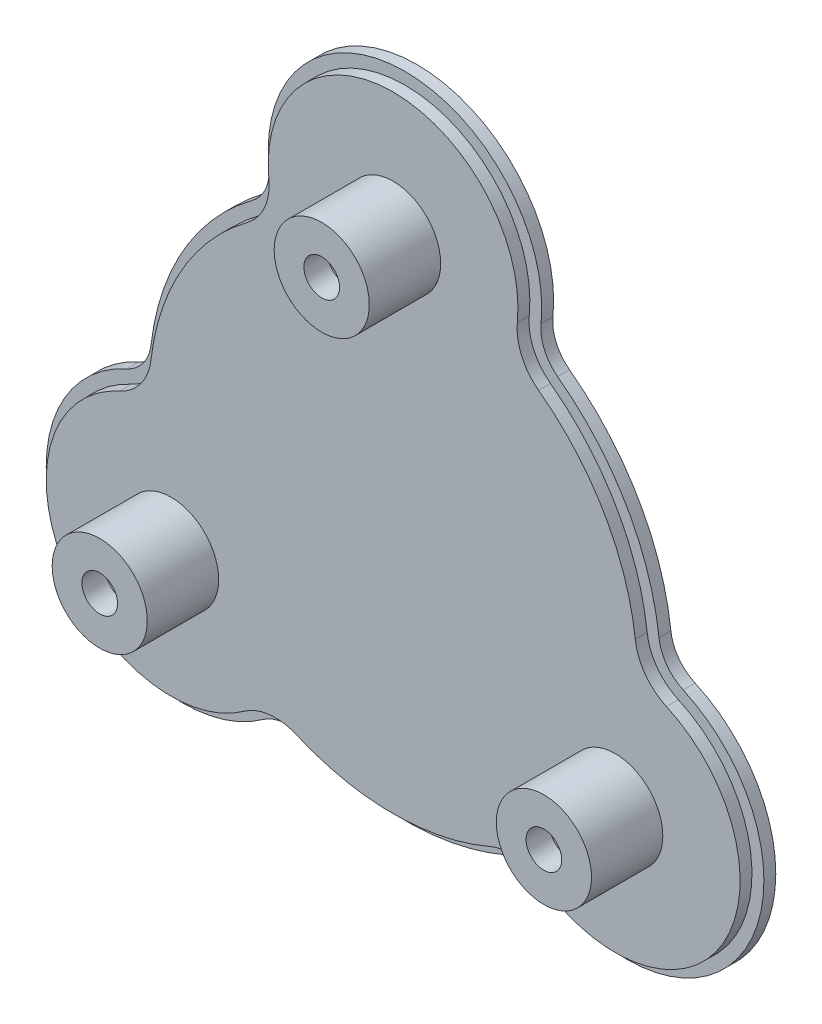
SolidWorks part; units mm, degrees
material "PE Low Density Film"
ref_plane "Front Plane" through (0, 0, 0) normal (0, 0, 1) x (1, 0, 0)
ref_plane "Top Plane" through (0, 0, 0) normal (0, 1, 0) x (1, 0, 0)
ref_plane "Right Plane" through (0, 0, 0) normal (1, 0, 0) x (0, 0, -1)
sketch "Sketch1" plane through (0, 0, 0) normal (0, 0, 1) x (1, 0, 0)
  arc A1 (22.8772, 40.8196) -> (-22.8904, 40.8122) centre (-0.007, 43.1247) ccw
  circle A2 centre (-0.007, 43.1247) radius 5.5
  arc A3 (23.9122, -40.222) -> (46.7896, -0.5824) centre (37.3506, -21.5563) ccw
  circle A4 centre (37.3506, -21.5563) radius 5.5
  arc A5 (-46.7894, -0.5976) -> (-23.8991, -40.2298) centre (-37.3436, -21.5684) ccw
  circle A6 centre (-37.3436, -21.5684) radius 5.5
  arc A7 (-25.6753, 34.4932) -> (-42.7112, 4.975) centre (0, 0) ccw
  arc A8 (42.7096, 4.9888) -> (25.6641, 34.5015) centre (0, 0) ccw
  arc A9 (-17.0343, -39.482) -> (17.0471, -39.4765) centre (0, 0) ccw
  arc A10 (22.8772, 40.8196) -> (25.6641, 34.5015) centre (29.842, 40.118) ccw
  arc A11 (42.7096, 4.9888) -> (46.7896, -0.5824) centre (49.6623, 5.801) ccw
  arc A12 (23.9122, -40.222) -> (17.0471, -39.4765) centre (19.8223, -45.9029) ccw
  arc A13 (-17.0343, -39.482) -> (-23.8991, -40.2298) centre (-19.8074, -45.9093) ccw
  arc A14 (-46.7894, -0.5976) -> (-42.7112, 4.975) centre (-49.6642, 5.7849) ccw
  arc A15 (-25.6753, 34.4932) -> (-22.8904, 40.8122) centre (-29.855, 40.1084) ccw
  point P14 (0, 0)
  point P23 (-20.8553, -37.6039)
  dimension "D2" = 46
  dimension "D3" = 11
  dimension "D1" = 7
  dimension "D4" = 3
extrude "Boss-Extrude1" add sketch "Sketch1" along normal blind 4
sketch "Sketch2" plane through (0, 0, 4) normal (0, 0, 1) x (1, 0, 0)
  arc A0 (-24.4811, 32.8889) -> (-40.7247, 4.7436) centre (0, 0) ccw
  arc A1 (-45.968, -2.4211) -> (-40.7247, 4.7436) centre (-49.6642, 5.7849) ccw
  arc A2 (-45.968, -2.4211) -> (-25.0682, -38.6071) centre (-37.3436, -21.5684) ccw
  arc A3 (-16.242, -37.6457) -> (-25.0682, -38.6071) centre (-19.8074, -45.9093) ccw
  arc A4 (-16.242, -37.6457) -> (16.2543, -37.6404) centre (0, 0) ccw
  arc A5 (25.0808, -38.5989) -> (16.2543, -37.6404) centre (19.8223, -45.9029) ccw
  arc A6 (25.0808, -38.5989) -> (45.9688, -2.4062) centre (37.3506, -21.5563) ccw
  arc A7 (40.7231, 4.7568) -> (45.9688, -2.4062) centre (49.6623, 5.801) ccw
  arc A8 (40.7231, 4.7568) -> (24.4704, 32.8968) centre (0, 0) ccw
  arc A9 (20.8873, 41.02) -> (24.4704, 32.8968) centre (29.842, 40.118) ccw
  arc A10 (20.8873, 41.02) -> (-20.9006, 41.0133) centre (-0.007, 43.1247) ccw
  arc A11 (-24.4811, 32.8889) -> (-20.9006, 41.0133) centre (-29.855, 40.1084) ccw
  arc A12 (22.8772, 40.8196) -> (25.6641, 34.5015) centre (29.842, 40.118) ccw
  arc A13 (22.8772, 40.8196) -> (-22.8904, 40.8122) centre (-0.007, 43.1247) ccw
  arc A14 (-25.6753, 34.4932) -> (-22.8904, 40.8122) centre (-29.855, 40.1084) ccw
  arc A15 (-25.6753, 34.4932) -> (-42.7112, 4.975) centre (0, 0) ccw
  arc A16 (-46.7894, -0.5976) -> (-42.7112, 4.975) centre (-49.6642, 5.7849) ccw
  arc A17 (-46.7894, -0.5976) -> (-23.8991, -40.2298) centre (-37.3436, -21.5684) ccw
  arc A18 (-17.0343, -39.482) -> (-23.8991, -40.2298) centre (-19.8074, -45.9093) ccw
  arc A19 (-17.0343, -39.482) -> (17.0471, -39.4765) centre (0, 0) ccw
  arc A20 (23.9122, -40.222) -> (17.0471, -39.4765) centre (19.8223, -45.9029) ccw
  arc A21 (23.9122, -40.222) -> (46.7896, -0.5824) centre (37.3506, -21.5563) ccw
  arc A22 (42.7096, 4.9888) -> (46.7896, -0.5824) centre (49.6623, 5.801) ccw
  arc A23 (42.7096, 4.9888) -> (25.6641, 34.5015) centre (0, 0) ccw
  arc A24 (22.8772, 40.8196) -> (25.6641, 34.5015) centre (29.842, 40.118) ccw
  arc A25 (22.8772, 40.8196) -> (-22.8904, 40.8122) centre (-0.007, 43.1247) ccw
  arc A26 (-25.6753, 34.4932) -> (-22.8904, 40.8122) centre (-29.855, 40.1084) ccw
  arc A27 (-25.6753, 34.4932) -> (-42.7112, 4.975) centre (0, 0) ccw
  arc A28 (-46.7894, -0.5976) -> (-42.7112, 4.975) centre (-49.6642, 5.7849) ccw
  arc A29 (-46.7894, -0.5976) -> (-23.8991, -40.2298) centre (-37.3436, -21.5684) ccw
  arc A30 (-17.0343, -39.482) -> (-23.8991, -40.2298) centre (-19.8074, -45.9093) ccw
  arc A31 (-17.0343, -39.482) -> (17.0471, -39.4765) centre (0, 0) ccw
  arc A32 (23.9122, -40.222) -> (17.0471, -39.4765) centre (19.8223, -45.9029) ccw
  arc A33 (23.9122, -40.222) -> (46.7896, -0.5824) centre (37.3506, -21.5563) ccw
  arc A34 (42.7096, 4.9888) -> (46.7896, -0.5824) centre (49.6623, 5.801) ccw
  arc A35 (42.7096, 4.9888) -> (25.6641, 34.5015) centre (0, 0) ccw
  dimension "D2" = 2
extrude "Cut-Extrude1" cut sketch "Sketch2" against normal blind 2 contours A24 A35 A34 A33 A32 A31 A30 A29 A28 A27 A26 A25 | A0 A1 A2 A3 A4 A5 A6 A7 A8 A9 A10 A11
sketch "Sketch4" plane through (0, 0, 0) normal (0, 0, -1) x (-1, 0, 0)
  circle A0 centre (0.007, 43.1247) radius 8
  circle A1 centre (-37.3506, -21.5563) radius 8
  circle A2 centre (37.3436, -21.5684) radius 8
  dimension "D1" = 16
  dimension "D2" = 16
  dimension "D3" = 16
extrude "Boss-Extrude2" add sketch "Sketch4" against normal blind 16
sketch "Sketch6" plane through (0, 0, 16) normal (0, 0, 1) x (1, 0, 0)
  circle A0 centre (-0.007, 43.1247) radius 3
  circle A1 centre (-37.3436, -21.5684) radius 3
  circle A2 centre (37.3506, -21.5563) radius 3
  dimension "D1" = 6
extrude "Cut-Extrude2" cut sketch "Sketch6" against normal blind 4
sketch "Sketch7" plane through (0, 0, 12) normal (0, 0, 1) x (1, 0, 0)
  circle A0 centre (-0.007, 43.1247) radius 5.5
  circle A1 centre (-37.3436, -21.5684) radius 5.5
  circle A2 centre (37.3506, -21.5563) radius 5.5
  dimension "D1" = 11
extrude "Cut-Extrude3" cut sketch "Sketch7" against normal through all
equation "\"A\" = 46"
equation "\"B\" = 16"
equation "\"C\"= 2"
equation "\"D2@Sketch1\"=\"A\""
equation "\"D1@Boss-Extrude1\"=\"C\"*2"
equation "\"D2@Sketch2\"=\"C\""
equation "\"D1@Cut-Extrude1\"=\"C\""
equation "\"D1@Boss-Extrude2\"=\"B\""
equation "\"D1@Cut-Extrude2\"=\"C\"*2"
